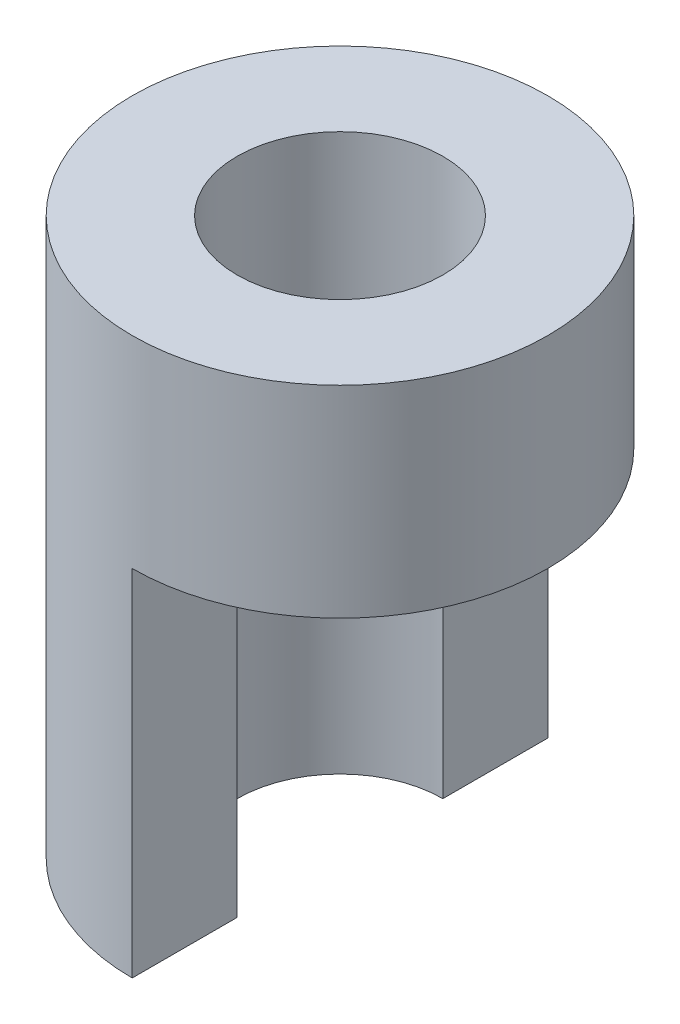
SolidWorks part; units mm, degrees
ref_plane "前基準面" through (0, 0, 0) normal (0, 0, 1) x (1, 0, 0)
ref_plane "上基準面" through (0, 0, 0) normal (0, 1, 0) x (1, 0, 0)
ref_plane "右基準面" through (0, 0, 0) normal (1, 0, 0) x (0, 0, -1)
sketch "草圖1" plane through (0, 0, 0) normal (0, 1, 0) x (1, 0, 0)
  line L0 (0, -1000) -> (0, 49000) construction
  arc A0 (0, 5.1) -> (0, -5.1) centre (0, 0) ccw
  dimension "D1" = 10.2
extrude "伸長-薄件1" add sketch "草圖1" along normal blind 27.58 thin
sketch "草圖2" plane through (0, 0, 0) normal (1, 0, 0) x (0, 0, -1)
  line L1 (5.1, 0) -> (7.2314, 0)
  line L2 (5.1, 0) -> (5.1, 3)
  line L5 (-12.6274, 12.05) -> (11.8932, 12.05) construction
  line L6 (-12.6274, 12.05) -> (-12.6274, 3) construction
  line L7 (-12.6274, 3) -> (11.8932, 3) construction
  line L8 (11.8932, 12.05) -> (11.8932, 3) construction
  dimension "D2" = 9.05
sketch "草圖3" plane through (0, 27.58, 0) normal (0, 1, 0) x (1, 0, 0)
  line L0 (0, -1000) -> (0, 49000) construction
  arc A0 (0, -5.1) -> (0, 5.1) centre (0, 0) ccw
extrude "伸長-薄件2" add sketch "草圖3" against normal blind 10 thin
sketch "草圖4" plane through (0, 27.58, 0) normal (0, 1, 0) x (1, 0, 0)
  circle A0 centre (0, 0) radius 13.785
  dimension "D1" = 27.57
